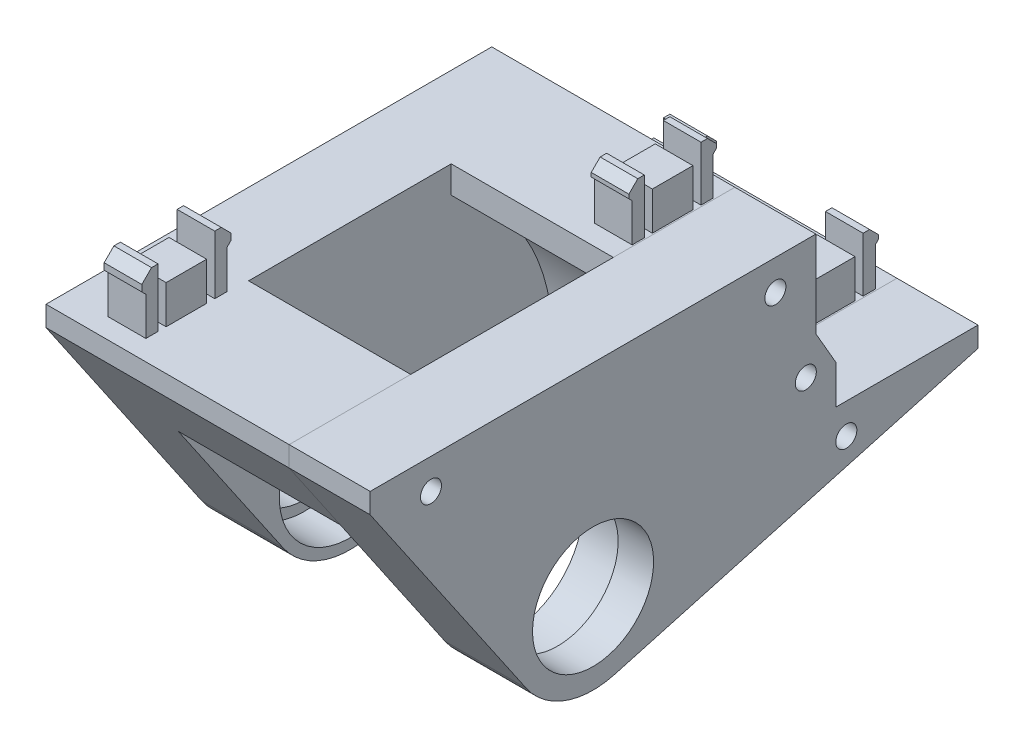
SolidWorks part; units mm, degrees
ref_plane "Front Plane" through (0, 0, 0) normal (0, 0, 1) x (1, 0, 0)
ref_plane "Top Plane" through (0, 0, 0) normal (0, 1, 0) x (1, 0, 0)
ref_plane "Right Plane" through (0, 0, 0) normal (1, 0, 0) x (0, 0, -1)
ref_plane "TopPlate" through (0, 25.4, 0) normal (0, 1, 0) x (1, 0, 0)
ref_plane "BottomPlate" through (0, 0, 0) normal (0, 1, 0) x (1, 0, 0)
sketch "Slots" plane through (0, 25.4, 0) normal (0, 1, 0) x (1, 0, 0)
  line L0 (-15.875, 44.45) -> (-9.525, 44.45) construction
  line L1 (-41.275, 44.45) -> (-34.925, 44.45) construction
  line L2 (-41.275, 44.45) -> (-41.275, 31.75) construction
  line L3 (-41.275, 31.75) -> (-34.925, 31.75) construction
  line L4 (-34.925, 44.45) -> (-34.925, 31.75) construction
  line L5 (-41.275, 44.45) -> (-34.925, 31.75) construction
  line L6 (-41.275, 31.75) -> (-34.925, 44.45) construction
  line L7 (-15.875, 44.45) -> (-15.875, 31.75) construction
  line L8 (-15.875, 31.75) -> (-9.525, 31.75) construction
  line L9 (-9.525, 44.45) -> (-9.525, 31.75) construction
  line L10 (-15.875, 44.45) -> (-9.525, 31.75) construction
  line L11 (-15.875, 31.75) -> (-9.525, 44.45) construction
  line L12 (9.525, 44.45) -> (15.875, 44.45) construction
  line L13 (9.525, 44.45) -> (9.525, 31.75) construction
  line L14 (9.525, 31.75) -> (15.875, 31.75) construction
  line L15 (15.875, 44.45) -> (15.875, 31.75) construction
  line L16 (9.525, 44.45) -> (15.875, 31.75) construction
  line L17 (9.525, 31.75) -> (15.875, 44.45) construction
  line L18 (34.925, 44.45) -> (41.275, 44.45) construction
  line L19 (34.925, 44.45) -> (34.925, 31.75) construction
  line L20 (34.925, 31.75) -> (41.275, 31.75) construction
  line L21 (41.275, 44.45) -> (41.275, 31.75) construction
  line L22 (34.925, 44.45) -> (41.275, 31.75) construction
  line L23 (34.925, 31.75) -> (41.275, 44.45) construction
  line L24 (-15.875, 19.05) -> (-9.525, 19.05) construction
  line L25 (-15.875, 19.05) -> (-15.875, 6.35) construction
  line L26 (-15.875, 6.35) -> (-9.525, 6.35) construction
  line L27 (-9.525, 19.05) -> (-9.525, 6.35) construction
  line L28 (-15.875, 19.05) -> (-9.525, 6.35) construction
  line L29 (-15.875, 6.35) -> (-9.525, 19.05) construction
  line L30 (9.525, 19.05) -> (15.875, 19.05) construction
  line L31 (9.525, 19.05) -> (9.525, 6.35) construction
  line L32 (9.525, 6.35) -> (15.875, 6.35) construction
  line L33 (15.875, 19.05) -> (15.875, 6.35) construction
  line L34 (9.525, 19.05) -> (15.875, 6.35) construction
  line L35 (9.525, 6.35) -> (15.875, 19.05) construction
  line L36 (34.925, 19.05) -> (41.275, 19.05) construction
  line L37 (34.925, 19.05) -> (34.925, 6.35) construction
  line L38 (34.925, 6.35) -> (41.275, 6.35) construction
  line L39 (41.275, 19.05) -> (41.275, 6.35) construction
  line L40 (34.925, 19.05) -> (41.275, 6.35) construction
  line L41 (34.925, 6.35) -> (41.275, 19.05) construction
  line L42 (-15.875, -6.35) -> (-9.525, -6.35) construction
  line L43 (-15.875, -6.35) -> (-15.875, -19.05) construction
  line L44 (-15.875, -19.05) -> (-9.525, -19.05) construction
  line L45 (-9.525, -6.35) -> (-9.525, -19.05) construction
  line L46 (-15.875, -6.35) -> (-9.525, -19.05) construction
  line L47 (-15.875, -19.05) -> (-9.525, -6.35) construction
  line L48 (9.525, -6.35) -> (15.875, -6.35) construction
  line L49 (9.525, -6.35) -> (9.525, -19.05) construction
  line L50 (9.525, -19.05) -> (15.875, -19.05) construction
  line L51 (15.875, -6.35) -> (15.875, -19.05) construction
  line L52 (9.525, -6.35) -> (15.875, -19.05) construction
  line L53 (9.525, -19.05) -> (15.875, -6.35) construction
  line L54 (34.925, -6.35) -> (41.275, -6.35) construction
  line L55 (34.925, -6.35) -> (34.925, -19.05) construction
  line L56 (34.925, -19.05) -> (41.275, -19.05) construction
  line L57 (41.275, -6.35) -> (41.275, -19.05) construction
  line L58 (34.925, -6.35) -> (41.275, -19.05) construction
  line L59 (34.925, -19.05) -> (41.275, -6.35) construction
  line L60 (-15.875, -31.75) -> (-9.525, -31.75) construction
  line L61 (-15.875, -31.75) -> (-15.875, -44.45) construction
  line L62 (-15.875, -44.45) -> (-9.525, -44.45) construction
  line L63 (-9.525, -31.75) -> (-9.525, -44.45) construction
  line L64 (-15.875, -31.75) -> (-9.525, -44.45) construction
  line L65 (-15.875, -44.45) -> (-9.525, -31.75) construction
  line L66 (9.525, -31.75) -> (15.875, -31.75) construction
  line L67 (9.525, -31.75) -> (9.525, -44.45) construction
  line L68 (9.525, -44.45) -> (15.875, -44.45) construction
  line L69 (15.875, -31.75) -> (15.875, -44.45) construction
  line L70 (9.525, -31.75) -> (15.875, -44.45) construction
  line L71 (9.525, -44.45) -> (15.875, -31.75) construction
  line L72 (34.925, -31.75) -> (41.275, -31.75) construction
  line L73 (34.925, -31.75) -> (34.925, -44.45) construction
  line L74 (34.925, -44.45) -> (41.275, -44.45) construction
  line L75 (41.275, -31.75) -> (41.275, -44.45) construction
  line L76 (34.925, -31.75) -> (41.275, -44.45) construction
  line L77 (34.925, -44.45) -> (41.275, -31.75) construction
  line L78 (-41.275, 19.05) -> (-34.925, 19.05) construction
  line L79 (-41.275, 19.05) -> (-41.275, 6.35) construction
  line L80 (-41.275, 6.35) -> (-34.925, 6.35) construction
  line L81 (-34.925, 19.05) -> (-34.925, 6.35) construction
  line L82 (-41.275, 19.05) -> (-34.925, 6.35) construction
  line L83 (-41.275, 6.35) -> (-34.925, 19.05) construction
  line L84 (-41.275, -6.35) -> (-34.925, -6.35) construction
  line L85 (-41.275, -6.35) -> (-41.275, -19.05) construction
  line L86 (-41.275, -19.05) -> (-34.925, -19.05) construction
  line L87 (-34.925, -6.35) -> (-34.925, -19.05) construction
  line L88 (-41.275, -6.35) -> (-34.925, -19.05) construction
  line L89 (-41.275, -19.05) -> (-34.925, -6.35) construction
  line L90 (-41.275, -31.75) -> (-34.925, -31.75) construction
  line L91 (-41.275, -31.75) -> (-41.275, -44.45) construction
  line L92 (-41.275, -44.45) -> (-34.925, -44.45) construction
  line L93 (-34.925, -31.75) -> (-34.925, -44.45) construction
  line L94 (-41.275, -31.75) -> (-34.925, -44.45) construction
  line L95 (-41.275, -44.45) -> (-34.925, -31.75) construction
  line L96 (-47.625, 44.45) -> (-47.625, -50.8)
  line L97 (-47.625, -50.8) -> (41.275, -50.8)
  point P0 (-38.1, 38.1)
  point P5 (0, 0)
  point P8 (-12.7, 38.1)
  point P13 (12.7, 38.1)
  point P18 (38.1, 38.1)
  point P23 (-12.7, 12.7)
  point P28 (12.7, 12.7)
  point P33 (38.1, 12.7)
  point P38 (-12.7, -12.7)
  point P43 (12.7, -12.7)
  point P48 (38.1, -12.7)
  point P53 (-12.7, -38.1)
  point P58 (12.7, -38.1)
  point P63 (38.1, -38.1)
  point P68 (-38.1, 12.7)
  point P73 (-38.1, -12.7)
  point P78 (-38.1, -38.1)
  dimension "D3" = 38.1
  dimension "D4" = 38.1
  dimension "D5" = 12.7
  dimension "D6" = 6.35
  dimension "D7" = 25.4
  dimension "D8" = 25.4
  dimension "D9" = 6.35
  dimension "D10" = 6.35
  dimension "D1" = 4
  dimension "D2" = 4
sketch "Sketch4" plane through (0, 25.4, 0) normal (0, 1, 0) x (1, 0, 0)
  line L0 (-15.875, -31.75) -> (-9.525, -44.45) construction
  point P0 (-38.1, 12.7)
  point P1 (-38.1, -38.1)
  point P3 (-12.7, -38.1)
sketch "Lower Tabs" plane through (0, 0, 0) normal (0, 1, 0) x (1, 0, 0)
  line L0 (9.525, -31.75) -> (15.875, -44.45) construction
  line L2 (-41.1, 31.75) -> (-35.1, 31.75) construction
  line L3 (-41.1, 31.75) -> (-41.1, 44.45) construction
  line L4 (-41.1, 44.45) -> (-35.1, 44.45) construction
  line L5 (-35.1, 31.75) -> (-35.1, 44.45) construction
  line L6 (-41.1, 31.75) -> (-35.1, 44.45) construction
  line L7 (-41.1, 44.45) -> (-35.1, 31.75) construction
  point P0 (-38.1, 38.1)
  point P1 (-12.7, 38.1)
  point P3 (12.7, 12.7)
  point P5 (12.7, -38.1)
  point P7 (-38.1, 38.1)
  dimension "D2" = 12.7
  dimension "D1" = 6
sketch "Upper Tabs" plane through (0, 25.4, 0) normal (0, 1, 0) x (1, 0, 0)
  point P0 (-38.1, -38.1)
  point P1 (-12.7, 12.7)
sketch "Wheel Overlay" plane through (0, 0, 0) normal (1, 0, 0) x (0, 0, -1)
  line L0 (48.895, 25.4) -> (-48.895, 25.4) construction
  line L1 (48.895, 0) -> (-48.895, 0) construction
  circle A0 centre (-12.7, -12.7) radius 25.4
  circle A1 centre (-12.7, -12.7) radius 12.7
  point P3 (-12.7, -38.1)
  point P7 (-50.8, 25.4)
  dimension "D1" = 50.8
  dimension "D2" = 63.5
  dimension "D3" = 38.1
sketch "TopDown Overlay" plane through (0, 0, 0) normal (0, 1, 0) x (1, 0, 0)
  line L0 (-47.625, 44.45) -> (-47.625, -50.8) construction
  line L1 (-31.75, -38.1) -> (-12.7, -38.1)
  line L2 (-31.75, -38.1) -> (-31.75, 12.7)
  line L3 (-31.75, 12.7) -> (-12.7, 12.7)
  line L4 (-12.7, -38.1) -> (-12.7, 12.7)
  line L5 (-31.75, -38.1) -> (-12.7, 12.7) construction
  line L6 (-31.75, 12.7) -> (-12.7, -38.1) construction
  line L7 (-47.625, -50.8) -> (41.275, -50.8) construction
  line L8 (-47.625, -50.8) -> (3.175, -50.8)
  line L9 (-47.625, -50.8) -> (-47.625, 25.4)
  line L10 (-47.625, 25.4) -> (3.175, 25.4)
  line L11 (3.175, -50.8) -> (3.175, 25.4)
  line L12 (-34.925, -23.7) -> (-34.925, -1.7)
  line L13 (-9.525, -1.7) -> (-9.525, -23.7)
  line L14 (-22.225, 12.7) -> (-22.225, -38.1) construction
  line L15 (-43.9181, -12.7) -> (-4.2071, -12.7)
  line L28 (-34.925, -1.7) -> (-44.45, -1.7)
  line L29 (-44.45, -1.7) -> (-44.45, -23.7)
  line L30 (-44.45, -23.7) -> (-34.925, -23.7)
  line L31 (-9.525, -23.7) -> (0, -23.7)
  line L32 (0, -23.7) -> (0, -1.7)
  line L33 (0, -1.7) -> (-9.525, -1.7)
  point P0 (-22.225, -12.7)
  point P20 (-34.925, -12.7)
  point P21 (-9.525, -12.7)
  point P24 (-42.075, -1.7)
  dimension "D1" = 50.8
  dimension "D2" = 19.05
  dimension "D3" = 25.4
  dimension "D4" = 50.8
  dimension "D5" = 76.2
  dimension "D6" = 25.4
  dimension "D7" = 22
  dimension "D8" = 7.15
  dimension "D9" = 9.525
  dimension "D10" = 2.375
  dimension "D11" = 44.45
ref_plane "Plane1" through (-22.225, 0, 0) normal (1, 0, 0) x (0, 0, -1)
sketch "Sketch6" plane through (-22.225, 0, 0) normal (1, 0, 0) x (0, 0, -1)
  circle A0 centre (-12.7, -12.7) radius 11 construction
  circle A1 centre (-12.7, -12.7) radius 14.175
  circle A2 centre (-12.7, -12.7) radius 4.5
  dimension "D1" = 22
  dimension "D3" = 9
  dimension "D2" = 3.175
sketch "Sketch8" plane through (0, 0, 0) normal (0, 1, 0) x (1, 0, 0)
  line L1 (-31.75, 28.575) -> (-44.45, 28.575)
  line L2 (-31.75, 28.575) -> (-31.75, 47.625)
  line L3 (-31.75, 47.625) -> (-44.45, 47.625)
  line L4 (-44.45, 28.575) -> (-44.45, 47.625)
  line L5 (-31.75, 28.575) -> (-44.45, 47.625) construction
  line L6 (-31.75, 47.625) -> (-44.45, 28.575) construction
  point P0 (-38.1, 38.1)
  point P6 (-12.7, 38.1)
  point P12 (12.7, 12.7)
  point P18 (12.7, -38.1)
  dimension "D1" = 12.7
  dimension "D2" = 19.05
sketch "Sketch9" plane through (0, 25.4, 0) normal (0, 1, 0) x (1, 0, 0)
  line L1 (-44.45, -47.625) -> (-31.75, -47.625)
  line L2 (-44.45, -47.625) -> (-44.45, -28.575)
  line L3 (-44.45, -28.575) -> (-31.75, -28.575)
  line L4 (-31.75, -47.625) -> (-31.75, -28.575)
  line L5 (-44.45, -47.625) -> (-31.75, -28.575) construction
  line L6 (-44.45, -28.575) -> (-31.75, -47.625) construction
  point P0 (-38.1, -38.1)
  dimension "D1" = 12.7
  dimension "D2" = 19.05
sketch "Sketch10" plane through (-22.225, 0, 0) normal (1, 0, 0) x (0, 0, -1)
  line L0 (28.575, 0) -> (47.625, 0) construction
  line L1 (28.575, 0) -> (47.625, 0) construction
  line L2 (-50.8, 0) -> (25.4, 0) construction
  line L3 (-50.8, 0) -> (25.4, 0) construction
  line L4 (-47.625, 25.4) -> (-28.575, 25.4) construction
  line L5 (-47.625, 25.4) -> (-28.575, 25.4) construction
  line L6 (47.625, 0) -> (47.625, -6) construction
  line L7 (47.625, -6) -> (47.625, -9.175)
  line L8 (47.625, -9.175) -> (-9.3111, -24.9395)
  line L9 (-47.625, 25.4) -> (-47.625, 19.05) construction
  line L10 (-47.625, 19.05) -> (-47.625, 15.875)
  line L11 (-47.625, 15.875) -> (-23.1834, -19.8686)
  line L12 (-47.625, 19.05) -> (22.225, 19.05)
  line L13 (22.225, 19.05) -> (22.225, 5.4993)
  line L14 (22.225, 5.4993) -> (25.4, 0)
  line L15 (25.4, 0) -> (25.4, -6)
  line L16 (25.4, -6) -> (47.625, -6)
  arc A0 (-9.3111, -24.9395) -> (-12.7, 0) centre (-12.7, -12.7) ccw construction
  arc A1 (-12.7, 0) -> (-23.1834, -19.8686) centre (-12.7, -12.7) ccw construction
  arc A2 (-23.1834, -19.8686) -> (-19.0214, -23.715) centre (-12.7, -12.7) ccw
  arc A3 (-19.0214, -23.715) -> (-9.3111, -24.9395) centre (-12.7, -12.7) ccw construction
  arc A4 (-9.3111, -24.9395) -> (-19.0214, -23.715) centre (-12.7, -12.7) cw
  point P6 (12.7, 25.4)
  dimension "D1" = 6
  dimension "D3" = 25.4
  dimension "D2" = 3.175
  dimension "D4" = 6.35
  dimension "D5" = 3.175
  dimension "D6" = 30
  dimension "D7" = 9.525
extrude "Boss-Extrude4" add sketch "Sketch10" along normal mid plane 50.8
sketch "Sketch11" plane through (-22.225, 0, 0) normal (1, 0, 0) x (0, 0, -1)
  line L1 (3.175, 19.05) -> (3.175, 14.7963)
  line L2 (-28.575, 14.7963) -> (-28.575, 19.05)
  line L3 (22.225, 19.05) -> (-47.625, 19.05) construction
  line L4 (3.175, 14.7963) -> (-28.575, 14.7963) construction
  line L5 (-28.575, 19.05) -> (3.175, 19.05)
  circle A0 centre (-12.7, -12.7) radius 25.4 construction
  arc A1 (-28.575, 14.7963) -> (3.175, 14.7963) centre (-12.7, -12.7) ccw
  arc A2 (3.175, 14.7963) -> (-12.7, 19.05) centre (-12.7, -12.7) ccw construction
  arc A3 (-12.7, 19.05) -> (-28.575, 14.7963) centre (-12.7, -12.7) ccw construction
  dimension "D1" = 50.8
  dimension "D2" = 6.35
  dimension "D3" = 31.75
extrude "Cut-Extrude4" cut sketch "Sketch11" against normal mid plane 25.4
sketch "Sketch12" plane through (-9.525, 0, 0) normal (-1, 0, 0) x (0, 0, 1)
  circle A0 centre (12.7, -12.7) radius 11.075
  dimension "D1" = 22.15
extrude "Cut-Extrude5" cut sketch "Sketch12" against normal blind 7.15 and the other way offset from surface (32.55 mm away) 7.15 other way up to face at (-34.925, 1.337, 12.5925)
sketch "Sketch13" plane through (-47.625, 0, 0) normal (-1, 0, 0) x (0, 0, 1)
  circle A1 centre (12.7, -12.7) radius 11.075 construction
  circle A2 centre (12.7, -12.7) radius 11.075 construction
  circle A3 centre (12.7, -12.7) radius 9.4875
  dimension "D1" = 1.5875
extrude "Cut-Extrude6" cut sketch "Sketch13" against normal through all
ref_plane "Plane4" through (-25.4, 0, 0) normal (1, 0, 0) x (0, 0, -1)
sketch "Sketch22" plane through (0, -6, 0) normal (0, 1, 0) x (1, 0, 0)
  line L0 (-41.05, 31.75) -> (-35.15, 44.45) construction
  line L1 (-41.05, 44.45) -> (-35.15, 44.45)
  line L2 (-41.05, 44.45) -> (-41.05, 31.75)
  line L3 (-41.05, 31.75) -> (-35.15, 31.75)
  line L4 (-35.15, 44.45) -> (-35.15, 31.75)
  line L5 (-41.05, 44.45) -> (-35.15, 31.75) construction
  point P6 (-38.1, 38.1)
  dimension "D2" = 12.7
  dimension "D1" = 5.9
extrude "Boss-Extrude9" add sketch "Sketch22" along normal blind 6
sketch "Sketch23" plane through (0, 19.05, 0) normal (0, 1, 0) x (1, 0, 0)
  line L0 (-35.15, -31.75) -> (-41.05, -31.75)
  line L1 (-35.15, 19.05) -> (-41.05, 19.05)
  line L2 (-35.15, 19.05) -> (-35.15, 6.35)
  line L3 (-35.15, 6.35) -> (-41.05, 6.35)
  line L4 (-41.05, 19.05) -> (-41.05, 6.35)
  line L6 (-41.1, 31.75) -> (-35.1, 31.75) construction
  line L7 (-41.05, -31.75) -> (-41.05, -44.45)
  line L8 (-35.15, -31.75) -> (-35.15, -44.45)
  line L9 (-35.15, -44.45) -> (-41.05, -44.45)
  line L10 (-35.15, 19.05) -> (-35.15, -31.75) construction
  line L11 (-41.05, 6.35) -> (-35.15, 19.05) construction
  line L12 (-41.05, 19.05) -> (-35.15, 6.35) construction
  line L13 (-47.625, 22.225) -> (-47.625, -47.625) construction
  point P6 (-38.1, 12.7)
  dimension "D2" = 12.7
  dimension "D3" = 12.7
  dimension "D4" = 5.9
  dimension "D6" = 50.8
  dimension "D1" = 9.525
  dimension "D5" = 2
extrude "Boss-Extrude10" add sketch "Sketch23" along normal blind 6
sketch "Sketch25" plane through (-41.05, 0, 0) normal (-1, 0, 0) x (0, 0, 1)
  line L0 (-44.45, 0) -> (-42.545, 0)
  line L1 (-31.75, 0) -> (-44.45, 0) construction
  line L2 (-42.545, 0) -> (-42.545, 2.54)
  line L3 (-42.545, 2.54) -> (-43.561, 2.54)
  line L7 (-44.45, 0) -> (-44.45, -6) construction
  line L8 (-43.561, 2.54) -> (-44.958, 1.143)
  line L9 (-45.2755, 0.8255) -> (-44.958, 0.508) construction
  line L10 (-44.958, 1.143) -> (-44.958, 0.508)
  line L11 (-44.958, 1.143) -> (-45.2755, 0.8255) construction
  line L12 (-44.958, 0.508) -> (-44.45, 0)
  line L13 (-38.1, 0) -> (-38.1, 3.175) construction
  line L14 (-31.75, 0) -> (-33.655, 0)
  line L15 (-31.242, 0.508) -> (-31.75, 0)
  line L16 (-31.242, 1.143) -> (-31.242, 0.508)
  line L17 (-32.639, 2.54) -> (-31.242, 1.143)
  line L18 (-33.655, 0) -> (-33.655, 2.54)
  line L19 (-33.655, 2.54) -> (-32.639, 2.54)
  line M3 (-31.75, 0) -> (-44.45, 0)
  dimension "D1" = 1.905
  dimension "D2" = 2.54
  dimension "D3" = 1.016
  dimension "D4" = 0.508
  dimension "D5" = 135
extrude "Boss-Extrude11" add sketch "Sketch25" against normal up to surface (5.9 mm away) contours L10 L12 L2 L3 L8 M3 | L19 L18 L15 L16 L17 M3 up to face at (-35.15, -3, -38.1)
sketch "Sketch27" plane through (-41.05, 0, 0) normal (-1, 0, 0) x (0, 0, 1)
  line L0 (-19.05, 25.05) -> (-17.145, 25.05)
  line L1 (-17.145, 25.05) -> (-17.145, 27.59)
  line L2 (-17.145, 27.59) -> (-18.161, 27.59)
  line L3 (-18.161, 27.59) -> (-19.558, 26.193)
  line L4 (-19.8755, 25.8755) -> (-19.558, 25.558) construction
  line L5 (-19.558, 26.193) -> (-19.558, 25.558)
  line L6 (-19.558, 26.193) -> (-19.8755, 25.8755) construction
  line L7 (-19.558, 25.558) -> (-19.05, 25.05)
  line L10 (-12.7, 25.4) -> (-12.7, 28.575) construction
  line L11 (-6.35, 25.05) -> (-8.255, 25.05)
  line L12 (-5.842, 25.558) -> (-6.35, 25.05)
  line L13 (-5.842, 26.193) -> (-5.842, 25.558)
  line L14 (-7.239, 27.59) -> (-5.842, 26.193)
  line L15 (-8.255, 27.59) -> (-7.239, 27.59)
  line L16 (-8.255, 25.05) -> (-8.255, 27.59)
  line L17 (31.75, 25.05) -> (33.655, 25.05)
  line L18 (33.655, 25.05) -> (33.655, 28.225)
  line L19 (33.655, 28.225) -> (32.639, 28.225)
  line L20 (32.639, 28.225) -> (31.115, 26.701)
  line L21 (30.607, 26.193) -> (31.115, 25.685) construction
  line L22 (31.115, 26.701) -> (31.115, 25.685)
  line L23 (31.115, 26.701) -> (30.607, 26.193) construction
  line L24 (31.115, 25.685) -> (31.75, 25.05)
  line L27 (38.1, 25.4) -> (38.1, 28.575) construction
  line L28 (44.45, 25.05) -> (42.545, 25.05)
  line L29 (45.085, 25.685) -> (44.45, 25.05)
  line L30 (45.085, 26.701) -> (45.085, 25.685)
  line L31 (43.561, 28.225) -> (45.085, 26.701)
  line L32 (42.545, 28.225) -> (43.561, 28.225)
  line L33 (42.545, 25.05) -> (42.545, 28.225)
  line L34 (-19.05, 25.05) -> (-6.35, 25.05) construction
  line L35 (31.75, 25.05) -> (44.45, 25.05) construction
  dimension "D1" = 1.905
  dimension "D2" = 2.54
  dimension "D3" = 1.016
  dimension "D4" = 0.508
  dimension "D5" = 135
  dimension "D6" = 1.905
  dimension "D7" = 3.175
  dimension "D8" = 1.016
  dimension "D9" = 0.508
  dimension "D10" = 135
extrude "Boss-Extrude12" add sketch "Sketch27" against normal up to surface (5.9 mm away) up to face at (-35.15, 22.05, -12.7)
sketch "Sketch26" plane through (-41.05, 0, 0) normal (-1, 0, 0) x (0, 0, 1)
  line L0 (-31.75, 0) -> (-44.45, 0) construction
  line L1 (-42.545, 0) -> (-41.275, 0)
  line L2 (-42.545, 0) -> (-42.545, -6)
  line L3 (-42.545, -6) -> (-41.275, -6)
  line L4 (-41.275, 0) -> (-41.275, -6)
  line L5 (-42.545, 0) -> (-42.545, 2.54) construction
  line L6 (-47.625, -6) -> (-25.4, -6) construction
  line L7 (-38.1, 0) -> (-38.1, -6) construction
  line L8 (-44.45, -6) -> (-31.75, -6) construction
  line L9 (-33.655, 0) -> (-34.925, 0)
  line L10 (-33.655, -6) -> (-34.925, -6)
  line L11 (-33.655, 0) -> (-33.655, -6)
  line L12 (-34.925, 0) -> (-34.925, -6)
  dimension "D1" = 1.27
extrude "Cut-Extrude10" cut sketch "Sketch26" against normal through all
sketch "Sketch29" plane through (-41.05, 0, 0) normal (-1, 0, 0) x (0, 0, 1)
  line L0 (48.895, 25.4) -> (-48.895, 25.4) construction
  line L1 (-17.145, 25.4) -> (-15.875, 25.4)
  line L2 (-17.145, 25.4) -> (-17.145, 19.05)
  line L3 (-17.145, 19.05) -> (-15.875, 19.05)
  line L4 (-15.875, 25.4) -> (-15.875, 19.05)
  line L5 (-17.145, 25.05) -> (-17.145, 27.59) construction
  line L6 (-19.05, 19.05) -> (-6.35, 19.05) construction
  line L7 (-12.7, 25.4) -> (-12.7, 19.05) construction
  line L8 (-8.255, 19.05) -> (-9.525, 19.05)
  line L9 (-8.255, 25.4) -> (-9.525, 25.4)
  line L10 (-8.255, 25.4) -> (-8.255, 19.05)
  line L11 (-9.525, 25.4) -> (-9.525, 19.05)
  line L12 (31.75, 19.05) -> (44.45, 19.05) construction
  line L13 (33.655, 25.05) -> (34.925, 25.05)
  line L14 (33.655, 25.05) -> (33.655, 19.05)
  line L15 (33.655, 19.05) -> (34.925, 19.05)
  line L16 (34.925, 25.05) -> (34.925, 19.05)
  line L17 (38.1, 25.4) -> (38.1, 19.05) construction
  line L18 (42.545, 19.05) -> (41.275, 19.05)
  line L19 (42.545, 25.05) -> (42.545, 19.05)
  line L20 (42.545, 25.05) -> (41.275, 25.05)
  line L21 (41.275, 25.05) -> (41.275, 19.05)
  dimension "D1" = 1.27
  dimension "D2" = 1.27
extrude "Cut-Extrude11" cut sketch "Sketch29" against normal through all
mirror "Mirror1" about plane through (-25.4, 0, 0) normal (1, 0, 0) of "Cut-Extrude11", "Cut-Extrude10", "Boss-Extrude12", "Boss-Extrude11", "Boss-Extrude10", "Boss-Extrude9"
ref_plane "L/R mirror plane" through (76.2, 0, 0) normal (1, 0, 0) x (0, 0, -1)
ref_plane "F/B mirror plane" through (0, 0, -88.9) normal (0, 0, 1) x (1, 0, 0)
sketch "Sketch30" plane through (0, 19.05, 0) normal (0, 1, 0) x (1, 0, 0)
  line L1 (-16.9858, -47.4253) -> (-8.6207, -47.4253)
  line L2 (-16.9858, -47.4253) -> (-16.9858, -28.6278)
  line L3 (-16.9858, -28.6278) -> (-8.6207, -28.6278)
  line L4 (-8.6207, -47.4253) -> (-8.6207, -28.6278)
  line L5 (-16.9858, -47.4253) -> (-8.6207, -28.6278) construction
  line L6 (-16.9858, -28.6278) -> (-8.6207, -47.4253) construction
  line L7 (-33.0385, 4.9742) -> (-42.9004, 4.9742)
  line L8 (-33.0385, 4.9742) -> (-33.0385, 20.1996)
  line L9 (-33.0385, 20.1996) -> (-42.9004, 20.1996)
  line L10 (-42.9004, 4.9742) -> (-42.9004, 20.1996)
  line L11 (-33.0385, 4.9742) -> (-42.9004, 20.1996) construction
  line L12 (-33.0385, 20.1996) -> (-42.9004, 4.9742) construction
  point P0 (-12.8032, -38.0266)
  point P5 (-37.9694, 12.5869)
extrude "Cut-Extrude12" cut sketch "Sketch30" along normal through all
sketch "Sketch32" plane through (0, 19.05, 0) normal (0, 1, 0) x (1, 0, 0)
  line L0 (-9.525, -47.625) -> (-9.525, 48.9201)
  line L1 (3.175, -47.625) -> (-47.625, -47.625) construction
  line L2 (-9.525, 3.175) -> (-9.525, -28.575) construction
split "Split1" trim tools "Sketch32" bodies to split 158 resulting bodies 163 164
sketch "Sketch33" plane through (-9.525, 0, 0) normal (1, 0, 0) x (0, 0, -1)
  line L0 (-47.625, 19.05) -> (-47.625, 15.875) construction
  line L1 (-28.575, 19.05) -> (-47.625, 19.05) construction
  line L2 (22.225, 5.4993) -> (22.225, 19.05) construction
  line L3 (25.4, -6) -> (25.4, 0) construction
  line L4 (47.625, -6) -> (25.4, -6) construction
  circle A0 centre (-38.1, 14.2875) radius 1.65
  circle A1 centre (15.875, 14.2875) radius 1.65
  circle A2 centre (20.6375, 0.35) radius 1.65
  circle A3 centre (26.9875, -10.7625) radius 1.65
  dimension "D4" = 6.35
  dimension "D1" = 3.3
  dimension "D2" = 9.525
  dimension "D3" = 4.7625
  dimension "D5" = 4.7625
  dimension "D6" = 6.35
  dimension "D7" = 4.7625
  dimension "D8" = 1.5875
extrude "Cut-Extrude13" cut sketch "Sketch33" against normal mid plane 25.4
equation "\"D1@Sketch12\"=22.15mm"
equation "\"D4@Sketch23\"=6mm-.1mm"
equation "\"D1@Boss-Extrude10\"=6mm"
equation "\"D1@Sketch10\"=6mm"
equation "\"D1@Sketch22\"=6mm-.1mm"
equation "\"D1@Lower Tabs\"=6mm"
equation "\"D1@Sketch33\"=3.3mm"
